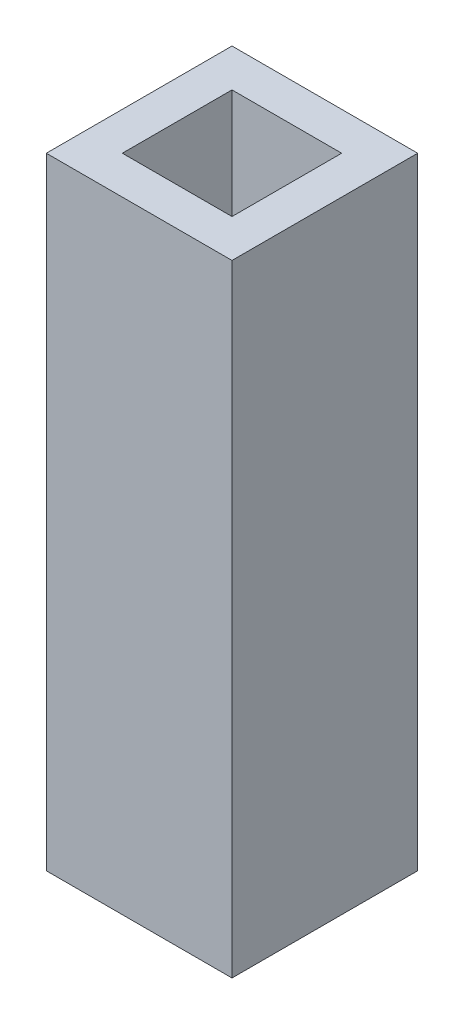
SolidWorks part; units mm, degrees
ref_plane "Спереди" through (0, 0, 0) normal (0, 0, 1) x (1, 0, 0)
ref_plane "Сверху" through (0, 0, 0) normal (0, 1, 0) x (1, 0, 0)
ref_plane "Справа" through (0, 0, 0) normal (1, 0, 0) x (0, 0, -1)
sketch "Эскиз1" plane through (0, 0, 0) normal (0, 1, 0) x (1, 0, 0)
  line L0 (1.27, 2.54) -> (1.27, 0) construction
  line L1 (0, 0) -> (2.54, 0)
  line L2 (0, 0) -> (0, 2.54)
  line L3 (0, 2.54) -> (2.54, 2.54)
  line L4 (2.54, 0) -> (2.54, 2.54)
  line L6 (0.52, 2.02) -> (2.02, 2.02)
  line L7 (0.52, 2.02) -> (0.52, 0.52)
  line L8 (0.52, 0.52) -> (2.02, 0.52)
  line L9 (2.02, 2.02) -> (2.02, 0.52)
  line L10 (0.52, 2.02) -> (2.02, 0.52) construction
  line L11 (0.52, 0.52) -> (2.02, 2.02) construction
  point P7 (1.27, 1.27)
  dimension "D1" = 2.54
  dimension "D2" = 1.5
extrude "Бобышка-Вытянуть1" add sketch "Эскиз1" along normal blind 8.5
